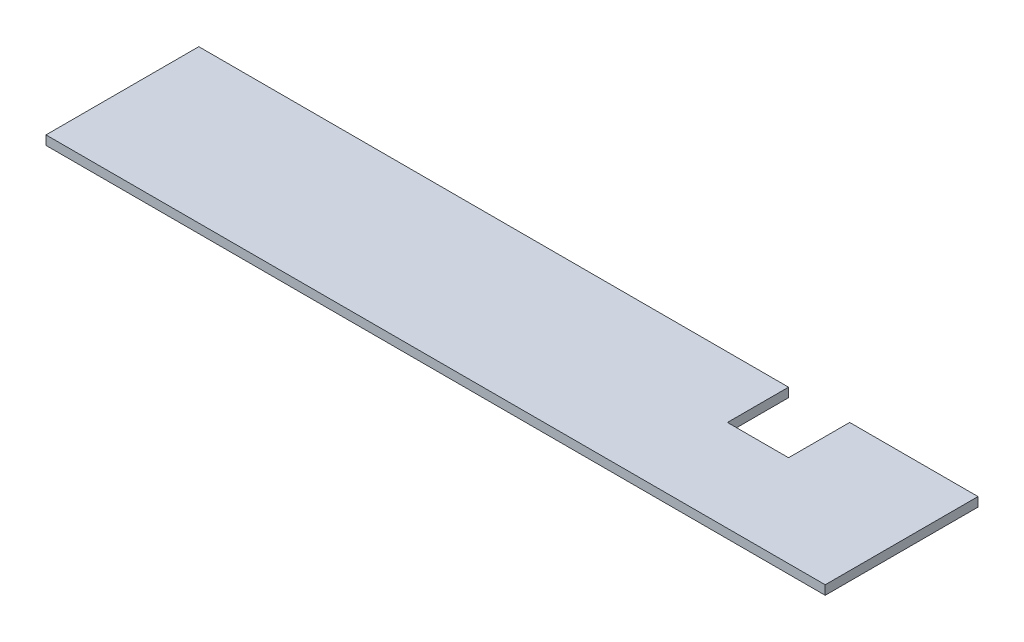
SolidWorks part; units mm, degrees
ref_plane "Front Plane" through (0, 0, 0) normal (0, 0, 1) x (1, 0, 0)
ref_plane "Top Plane" through (0, 0, 0) normal (0, 1, 0) x (1, 0, 0)
ref_plane "Right Plane" through (0, 0, 0) normal (1, 0, 0) x (0, 0, -1)
sketch "Sketch1" plane through (0, 0, 0) normal (0, 1, 0) x (1, 0, 0)
  line L1 (-42.0468, 23.5167) -> (212.9532, 23.5167)
  line L2 (-42.0468, 23.5167) -> (-42.0468, -26.4833)
  line L3 (-42.0468, -26.4833) -> (212.9532, -26.4833)
  line L4 (212.9532, 23.5167) -> (212.9532, -26.4833)
  dimension "D1" = 50
  dimension "D2" = 255
extrude "Boss-Extrude1" add sketch "Sketch1" along normal blind 3
sketch "Sketch2" plane through (0, 3, 0) normal (0, 1, 0) x (1, 0, 0)
  line L0 (212.9532, -26.4833) -> (212.9532, 23.5167) construction
  line L1 (170.9532, 23.5167) -> (150.9532, 23.5167)
  line L2 (170.9532, 23.5167) -> (170.9532, 3.5167)
  line L3 (170.9532, 3.5167) -> (150.9532, 3.5167)
  line L4 (150.9532, 23.5167) -> (150.9532, 3.5167)
  line L5 (212.9532, 23.5167) -> (-42.0468, 23.5167) construction
  dimension "D1" = 42
  dimension "D2" = 0
  dimension "D3" = 20
  dimension "D4" = 20
  dimension "D5" = 20
extrude "Cut-Extrude1" cut sketch "Sketch2" against normal blind 3
